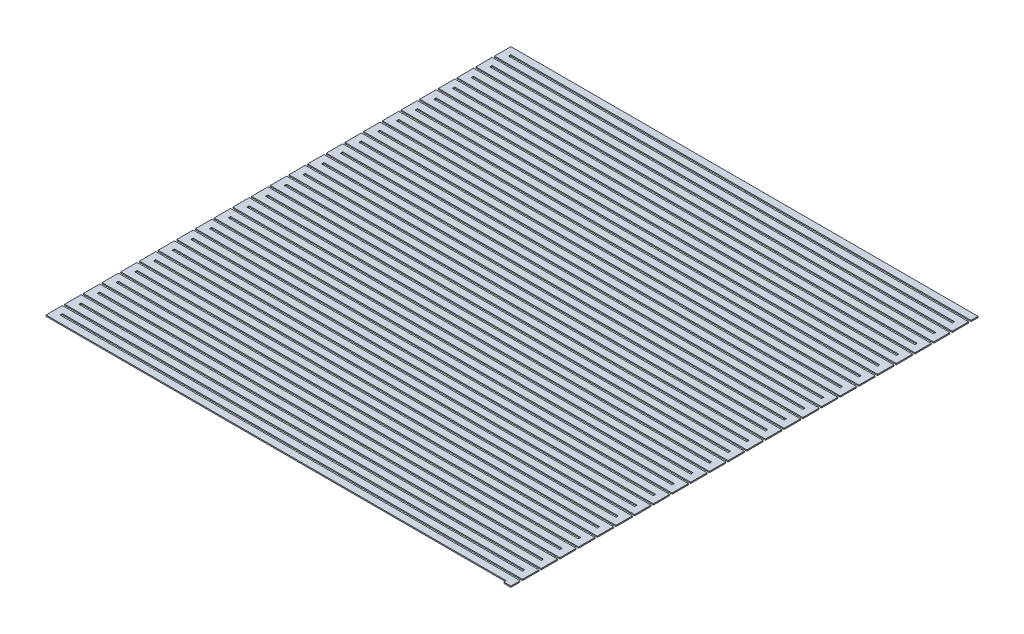
SolidWorks part; units mm, degrees
ref_plane "Front Plane" through (0, 0, 0) normal (0, 0, 1) x (1, 0, 0)
ref_plane "Top Plane" through (0, 0, 0) normal (0, 1, 0) x (1, 0, 0)
ref_plane "Right Plane" through (0, 0, 0) normal (1, 0, 0) x (0, 0, -1)
sketch "Base Guidlines" plane through (0, 0, 0) normal (0, 1, 0) x (1, 0, 0)
  line L0 (-4.5961, 9.2) -> (-4.5961, 8.5)
  line L1 (-10, -10) -> (10, -10)
  line L2 (-10, -10) -> (-10, 10)
  line L3 (-10, 10) -> (10, 10)
  line L4 (10, -10) -> (10, 10)
  line L5 (-10, -10) -> (10, 10) construction
  line L6 (-10, 10) -> (10, -10) construction
  line L7 (-10, 10) -> (10, 10)
  line L8 (-10, 10) -> (-10, 9.2)
  line L9 (-10, 9.2) -> (10, 9.2)
  line L10 (10, 10) -> (10, 9.2)
  line L11 (-4.5961, -9.2) -> (-4.5961, -8.5)
  line L12 (-10, -10) -> (10, -10)
  line L13 (-10, -10) -> (-10, -9.2)
  line L14 (-10, -9.2) -> (10, -9.2)
  line L15 (10, -10) -> (10, -9.2)
  line L17 (-10, -9.2) -> (10, -9.2)
  line L18 (-10, -9.2) -> (-10, -8.5)
  line L19 (-10, -8.5) -> (10, -8.5)
  line L20 (10, -9.2) -> (10, -8.5)
  line L21 (-10, 9.2) -> (10, 9.2)
  line L22 (-10, 9.2) -> (-10, 8.5)
  line L23 (-10, 8.5) -> (10, 8.5)
  line L24 (10, 9.2) -> (10, 8.5)
  point P0 (0, 0)
  dimension "D1" = 20
  dimension "D2" = 20
  dimension "D3" = 0.7
  dimension "D4" = 0.7
sketch "Mirror axis x" plane through (0, 0, 0) normal (0, 1, 0) x (1, 0, 0)
  line L0 (-10, 0) -> (10, 0)
  line L1 (-10, -10) -> (-10, 10) construction
  line L2 (10, -10) -> (10, 10) construction
sketch "TopBlock" plane through (0, 0, 0) normal (0, 1, 0) x (1, 0, 0)
  line L0 (-10, 10) -> (10, -10) construction
  line L1 (-10, 10) -> (-9.7, 10)
  line L2 (-10, 10) -> (-10, 9.7)
  line L3 (-10, 9.6) -> (-10, 9.3)
  line L4 (-9.7, 10) -> (10, 10)
  line L5 (-10, 9.7) -> (-10, 9.6)
  line L6 (-10, 9.3) -> (10, 9.3)
  line L7 (10, 9.3) -> (10, 9.6)
  line L8 (-9.7, 9.6) -> (-9.7, 9.7)
  line L9 (-9.7, 9.6) -> (10, 9.6)
  line L11 (-9.7, 9.7) -> (10, 9.7)
  line L12 (10, 9.7) -> (10, 10)
  dimension "D1" = 0.3
  dimension "D2" = 0.3
  dimension "D3" = 0.1
extrude "Extruded object" add sketch "TopBlock" along normal blind 0.05
sketch "Mirror axis y" plane through (0, 0, 0) normal (0, 1, 0) x (1, 0, 0)
  line L0 (0, 10) -> (0, -10)
  line L3 (10, 10) -> (-10, 10) construction
  dimension "D1" = 20
sketch "PatternMe" plane through (0, 0, 0) normal (0, 1, 0) x (1, 0, 0)
  line L0 (10, 9.3) -> (10, 9.2)
  line L1 (10, 9.2) -> (10, 8.9)
  line L2 (9.7, 9.2) -> (9.7, 9.3)
  line L3 (9.7, 9.3) -> (10, 9.3)
  line L4 (-10, 9.2) -> (-10, 8.9)
  line L5 (9.7, 9.2) -> (-10, 9.2)
  line L6 (-10, 9.2) -> (-10, 8.9)
  line L7 (10, 8.9) -> (-9.7, 8.9)
  line L8 (-10, 8.9) -> (-10, 8.8)
  line L9 (-9.7, 8.8) -> (10, 8.8)
  line L10 (-10, 8.8) -> (-10, 8.5)
  line L11 (-10, 8.5) -> (10, 8.5)
  line L12 (10, 8.8) -> (10, 8.5)
  line L13 (-9.7, 8.8) -> (-9.7, 8.9)
  dimension "D1" = 0.1
  dimension "D2" = 0.3
  dimension "D3" = 0.3
  dimension "D4" = 0.1
  dimension "D5" = 0.3
sketch "Sketch3" plane through (0, 0, 0) normal (0, 1, 0) x (1, 0, 0)
  line L0 (9.7, 9.2) -> (9.7, 9.3)
  line L1 (9.7, 9.3) -> (10, 9.3)
  line L2 (10, 9.3) -> (10, 8.9)
  line L3 (10, 8.9) -> (-9.7, 8.9)
  line L4 (-9.7, 8.9) -> (-9.7, 8.8)
  line L5 (-9.7, 8.8) -> (10, 8.8)
  line L6 (-9.7, 8.8) -> (10, 8.8) construction
  line L7 (10, 8.8) -> (10, 8.5)
  line L8 (10, 8.5) -> (-10, 8.5)
  line L9 (-10, 8.5) -> (-10, 9.2)
  line L10 (-10, 9.2) -> (9.7, 9.2)
extrude "Boss-Extrude1" add sketch "Sketch3" along normal blind 0.05
pattern_linear "LPattern2" count 24 spacing 0.8 along (0, 0, 1) of "Boss-Extrude1"
sketch "Sketch4" plane through (0, 0, 0) normal (0, 1, 0) x (1, 0, 0)
  line L0 (9.7, -10) -> (9.7, -9.9)
  line L1 (10, -9.9) -> (10, -10)
  line L2 (10, -10) -> (9.7, -10)
  line L3 (-10, -9.9) -> (10, -9.9) construction
  line L4 (9.7, -9.9) -> (10, -9.9)
  dimension "D1" = 0.1
extrude "Boss-Extrude2" add sketch "Sketch4" along normal blind 0.05
